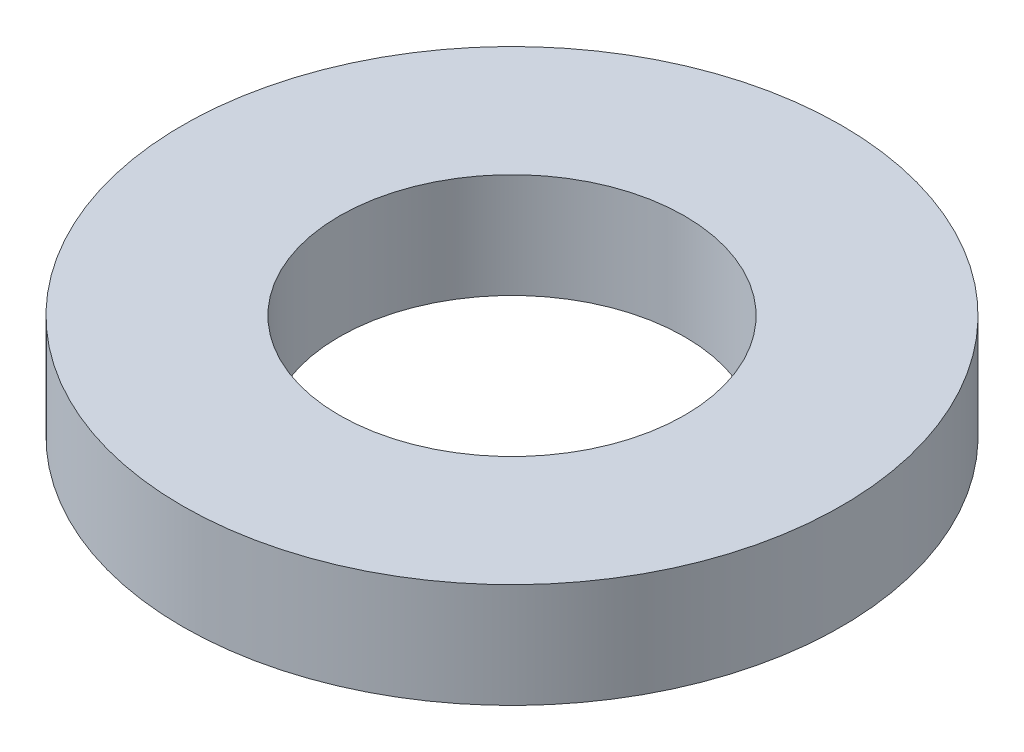
SolidWorks part; units mm, degrees
ref_plane "Front Plane" through (0, 0, 0) normal (0, 0, 1) x (1, 0, 0)
ref_plane "Top Plane" through (0, 0, 0) normal (0, 1, 0) x (1, 0, 0)
ref_plane "Right Plane" through (0, 0, 0) normal (1, 0, 0) x (0, 0, -1)
sketch "Sketch1" plane through (0, 0, 0) normal (0, 1, 0) x (1, 0, 0)
  circle A0 centre (0, 0) radius 16.5
  circle A1 centre (0, 0) radius 31.5
  dimension "D1" = 63
  dimension "D2" = 33
extrude "Boss-Extrude1" add sketch "Sketch1" along normal blind 10
